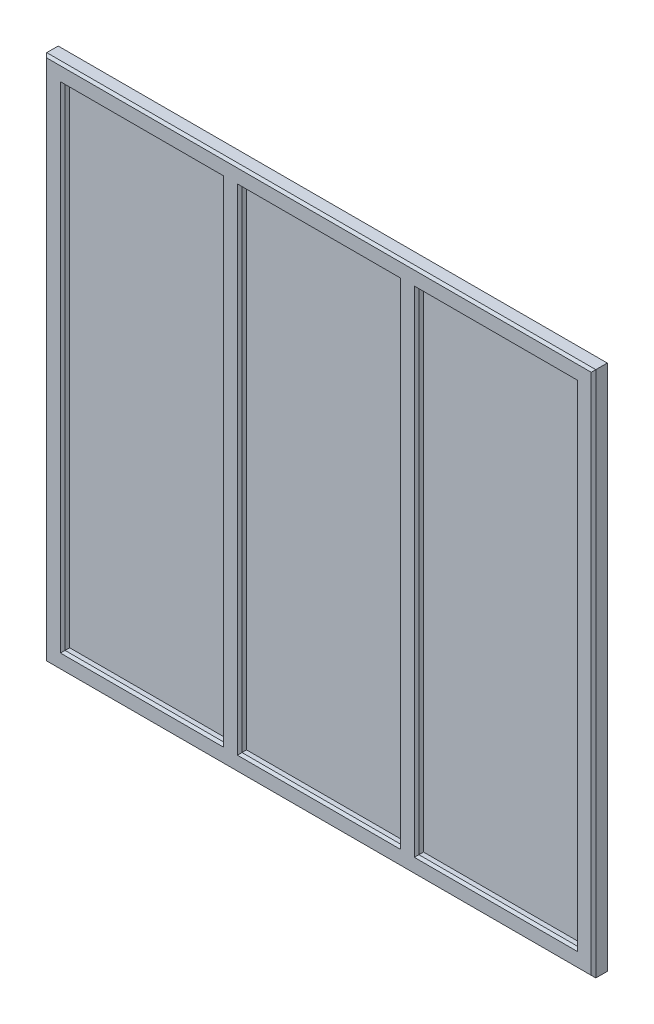
SolidWorks part; units mm, degrees
ref_plane "Спереди" through (0, 0, 0) normal (0, 0, 1) x (1, 0, 0)
ref_plane "Сверху" through (0, 0, 0) normal (0, 1, 0) x (1, 0, 0)
ref_plane "Справа" through (0, 0, 0) normal (1, 0, 0) x (0, 0, -1)
other "Configuration Table"
sketch "Эскиз1" plane through (0, 0, 0) normal (0, 0, 1) x (1, 0, 0)
  line L0 (80, 80) -> (80, 2220)
  line L1 (0, 0) -> (2397, 0)
  line L2 (0, 0) -> (0, 2300)
  line L3 (0, 2300) -> (2397, 2300)
  line L4 (2397, 0) -> (2397, 2300)
  line L5 (80, 2220) -> (772.3333, 2220)
  line L6 (2317, 80) -> (2317, 2220)
  line L7 (80, 80) -> (772.3333, 80)
  line L8 (772.3333, 2220) -> (772.3333, 80)
  line L9 (852.3333, 2220) -> (852.3333, 80)
  line L10 (1544.6667, 2220) -> (1544.6667, 80)
  line L11 (1624.6667, 2220) -> (1624.6667, 80)
  line L12 (852.3333, 2220) -> (1544.6667, 2220)
  line L13 (1624.6667, 2220) -> (2317, 2220)
  line L14 (80, 2220) -> (2317, 2220) construction
  line L15 (852.3333, 80) -> (1544.6667, 80)
  line L16 (1624.6667, 80) -> (2317, 80)
  line L17 (80, 80) -> (2317, 80) construction
  dimension "D1" = 2397
  dimension "D3" = 2300
  dimension "D4" = 80
  dimension "D5" = 80
  dimension "D2" = 80
extrude "Бобышка-Вытянуть1" add sketch "Эскиз1" along normal blind 60
chamfer "Фаска1" distance 10 angle 45 16 edges at (2317, 1150, 60) (426.1667, 2220, 60) (80, 1150, 60) (426.1667, 80, 60) (1198.5, 2300, 60) (2397, 1150, 60) (1198.5, 0, 60) (0, 1150, 60) (852.3333, 1150, 60) (1198.5, 80, 60) (1544.6667, 1150, 60) (1198.5, 2220, 60) (772.3333, 1150, 60) (1624.6667, 1150, 60) (1970.8333, 80, 60) (1970.8333, 2220, 60)
sketch "Эскиз2" plane through (0, 0, 0) normal (0, 0, -1) x (-1, 0, 0)
  line L1 (-2364.2704, 2265.9436) -> (-56.665, 2265.9436)
  line L2 (-2364.2704, 2265.9436) -> (-2364.2704, 48.4287)
  line L3 (-2364.2704, 48.4287) -> (-56.665, 48.4287)
  line L4 (-56.665, 2265.9436) -> (-56.665, 48.4287)
extrude "Бобышка-Вытянуть2" add sketch "Эскиз2" against normal blind 10 from offset 20 separate body
